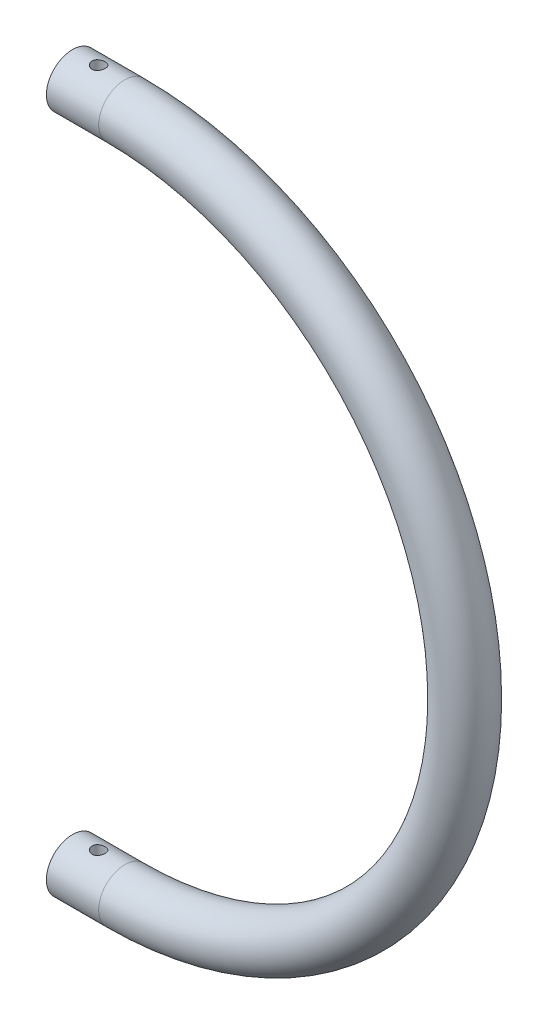
SolidWorks part; units mm, degrees
ref_plane "Plan de face" through (0, 0, 0) normal (0, 0, 1) x (1, 0, 0)
ref_plane "Plan de dessus" through (0, 0, 0) normal (0, 1, 0) x (1, 0, 0)
ref_plane "Plan de droite" through (0, 0, 0) normal (1, 0, 0) x (0, 0, -1)
sketch "Esquisse2" plane through (0, 0, 0) normal (0, 0, 1) x (1, 0, 0)
  arc A0 (0, -130) -> (0, 130) centre (0, 0) ccw
sweep "Balayage2" add path "Esquisse2" circular profile diameter 20 parameters "D3"=20
sketch "Esquisse38" plane through (0, 0, 0) normal (-1, 0, 0) x (0, 0, 1)
  circle A0 centre (0, -130) radius 10
extrude "Boss.-Extru.1" add sketch "Esquisse38" along normal blind 20
sketch "Esquisse39" plane through (0, 0, 0) normal (-1, 0, 0) x (0, 0, 1)
  circle A0 centre (0, 130) radius 10
extrude "Boss.-Extru.2" add sketch "Esquisse39" along normal blind 20
sketch "Esquisse41" plane through (0, 0, 0) normal (0, 1, 0) x (1, 0, 0)
  line L0 (0, 0) -> (-10, 0) construction
  circle A0 centre (-10, 0) radius 2.5
extrude "Enlèv. mat.-Extru.1" cut sketch "Esquisse41" against normal through all and the other way through all contours A0
